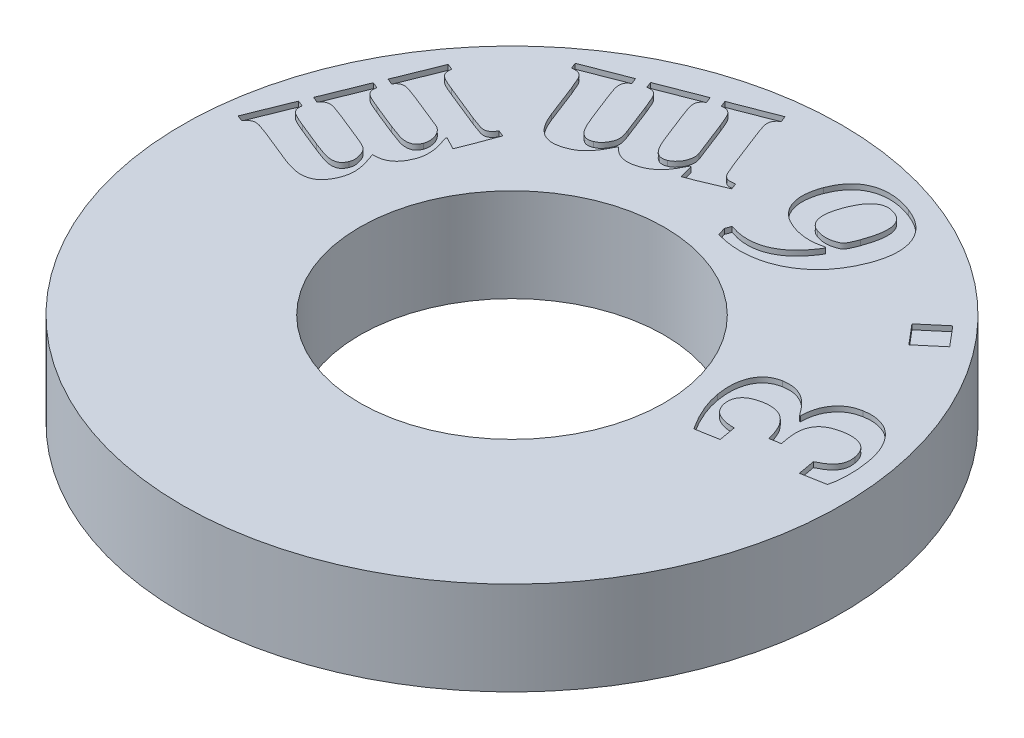
SolidWorks part; units mm, degrees
ref_plane "Front Plane" through (0, 0, 0) normal (0, 0, 1) x (1, 0, 0)
ref_plane "Top Plane" through (0, 0, 0) normal (0, 1, 0) x (1, 0, 0)
ref_plane "Right Plane" through (0, 0, 0) normal (1, 0, 0) x (0, 0, -1)
sketch "Sketch1" plane through (0, 0, 0) normal (0, 1, 0) x (1, 0, 0)
  circle A0 centre (0, 0) radius 12.7
  dimension "D1" = 25.4
extrude "Boss-Extrude1" add sketch "Sketch1" along normal blind 3.6
sketch "Sketch2" plane through (0, 0, 0) normal (0, -1, 0) x (-1, 0, 0)
  circle A0 centre (0, 0) radius 5.8674
  dimension "D1" = 11.7348
extrude "Cut-Extrude1" cut sketch "Sketch2" against normal through all
sketch "Sketch4" plane through (0, 3.6, 0) normal (0, 1, 0) x (1, 0, 0)
  circle A0 centre (0, 0) radius 12.0429 construction
  text T0 "<b>3.6mm</b>" font "Cambria" height 5.08
extrude "Cut-Extrude2" cut sketch "Sketch4" against normal blind 0.2
